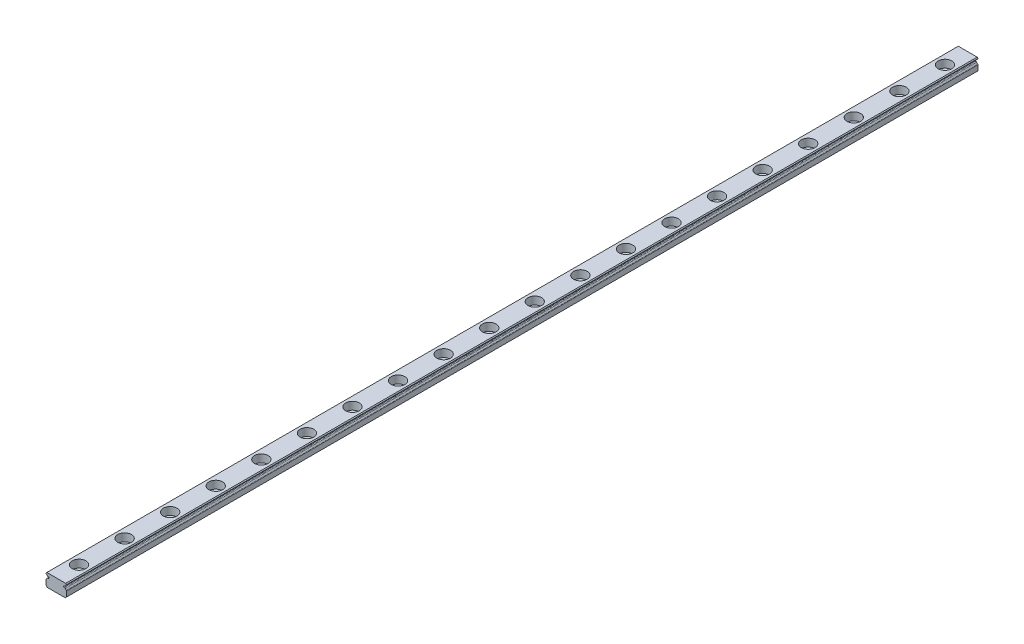
SolidWorks part; units mm, degrees
ref_plane "Front Plane" through (0, 0, 0) normal (0, 0, 1) x (1, 0, 0)
ref_plane "Top Plane" through (0, 0, 0) normal (0, 1, 0) x (1, 0, 0)
ref_plane "Right Plane" through (0, 0, 0) normal (1, 0, 0) x (0, 0, -1)
other "Configuration Table"
sketch "Sketch4" plane through (0, 0, 0) normal (0, 0, 1) x (1, 0, 0)
  line L1 (-4.5, -5.6) -> (4.5, -5.6)
  line L2 (-4.5, -5.6) -> (-4.5, 0)
  line L3 (-4.5, 0) -> (4.5, 0)
  line L4 (4.5, -5.6) -> (4.5, 0)
  line L5 (-4.5, -5.6) -> (4.5, 0) construction
  line L6 (-4.5, 0) -> (4.5, -5.6) construction
  point P0 (0, -2.8)
  dimension "D1" = 9
  dimension "D2" = 5.6
extrude "Boss-Extrude1" add sketch "Sketch4" along normal blind 400
sketch "Sketch5" plane through (0, 0, 0) normal (0, 0, 1) x (1, 0, 0)
  line L0 (-4.5, -5.6) -> (-4.5, 0) construction
  line L1 (-4.5, 0) -> (4.5, 0) construction
  arc A2 (-3.8246, -1.5019) -> (-3.8246, -1.6981) centre (-4.87, -1.6) ccw
  arc A3 (-3.8246, -1.5019) -> (-3.8246, -1.6981) centre (-3.52, -1.6) cw
  dimension "D2" = 1.05
  dimension "D3" = 0.37
  dimension "D1" = 0.32
  dimension "D4" = 0.98
  dimension "D5" = 1.6
extrude "Cut-Extrude1" cut sketch "Sketch5" along normal through all
mirror "Mirror3" about plane through (0, 0, 0) normal (1, 0, 0) of "Cut-Extrude1"
fillet "Fillet1" radius 0.3 8 edges at (-4.5, -2.5826, 200) (-4.5, -0.6174, 200) (-3.8246, -1.6981, 200) (-3.8246, -1.5019, 200) (4.5, -0.6174, 200) (4.5, -2.5826, 200) (3.8246, -1.5019, 200) (3.8246, -1.6981, 200)
chamfer "Chamfer1" distance 0.36 angle 45 2 edges at (-4.5, 0, 200) (4.5, 0, 200)
chamfer "Chamfer2" distance 0.56 angle 45 2 edges at (-4.5, -5.6, 200) (4.5, -5.6, 200)
sketch "Sketch7" plane through (0, 0, 0) normal (0, 1, 0) x (1, 0, 0)
  point P0 (0, -10)
  dimension "D1" = 10
hole_wizard "CBORE for M3 Hex Socket Head Cap Screw1" positions "Sketch7" profile "Sketch8" counterbore size "M3" standard "DIN" end condition through all
sketch "Sketch8" plane through (0, 0, 10) normal (1, 0, 0) x (0, 0, 1)
  line L0 (0, 0) -> (0, 5.6)
  line L1 (0, 5.6) -> (1.75, 5.6)
  line L3 (1.75, 5.6) -> (1.75, 3.4)
  line L4 (1.75, 3.4) -> (3, 3.4)
  line L5 (3, 3.4) -> (3, 0)
  line L7 (3, 0) -> (0, 0)
  line L11 (0, -6.35) -> (0, 107.95) construction
  dimension "Thru Hole Dia." = 3.5
  dimension "Thru Hole Depth" = 5.6
  dimension "C'Bore Dia." = 6
  dimension "C'Bore Depth" = 3.4
pattern_linear "LPattern1" count 20 spacing 20 along (0, 0, 1) of "CBORE for M3 Hex Socket Head Cap Screw1"
